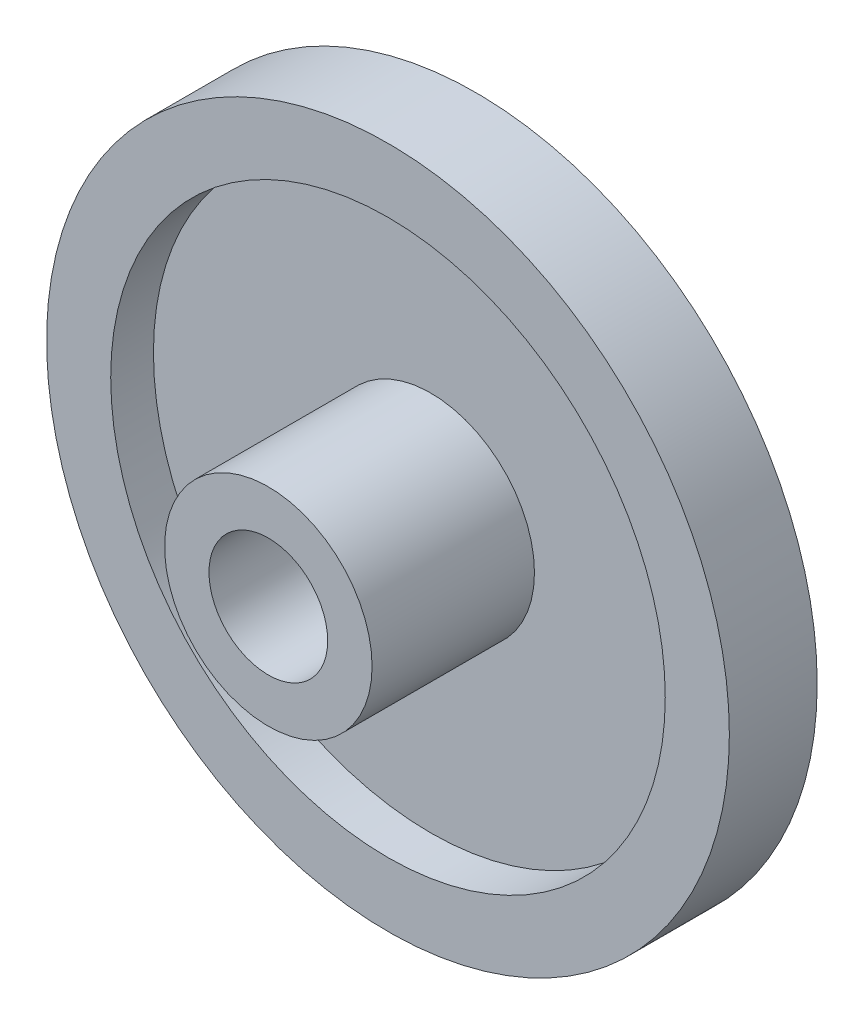
SolidWorks part; units mm, degrees
material "Delrin 2700 NC010, Low Viscosity Acetal Copolymer (SS)"
ref_plane "Front Plane" through (0, 0, 0) normal (0, 0, 1) x (1, 0, 0)
ref_plane "Top Plane" through (0, 0, 0) normal (0, 1, 0) x (1, 0, 0)
ref_plane "Right Plane" through (0, 0, 0) normal (1, 0, 0) x (0, 0, -1)
sketch "Sketch2" plane through (0, 0, 0) normal (1, 0, 0) x (0, 0, -1)
  line L0 (-114.8846, 0) -> (94.8572, 0) construction
  line L1 (0, 18.2626) -> (-4.699, 18.2626)
  line L2 (-4.699, 18.2626) -> (-4.699, 14.8336)
  line L3 (-4.699, 14.8336) -> (-2.413, 14.8336)
  line L4 (-2.413, 14.8336) -> (-2.413, 5.5499)
  line L5 (-11.0998, 3.175) -> (0, 3.175)
  line L6 (0, 3.175) -> (0, 18.2626)
  line L7 (-2.413, 5.5499) -> (-11.0998, 5.5499)
  line L8 (-11.0998, 5.5499) -> (-11.0998, 3.175)
  dimension "D1" = 2.413
  dimension "D2" = 4.699
  dimension "D3" = 6.35
  dimension "D4" = 11.0998
  dimension "D5" = 29.6672
  dimension "D6" = 36.5252
  dimension "D7" = 11.0998
revolve "Revolve1" add sketch "Sketch2" angle 360 about L0
